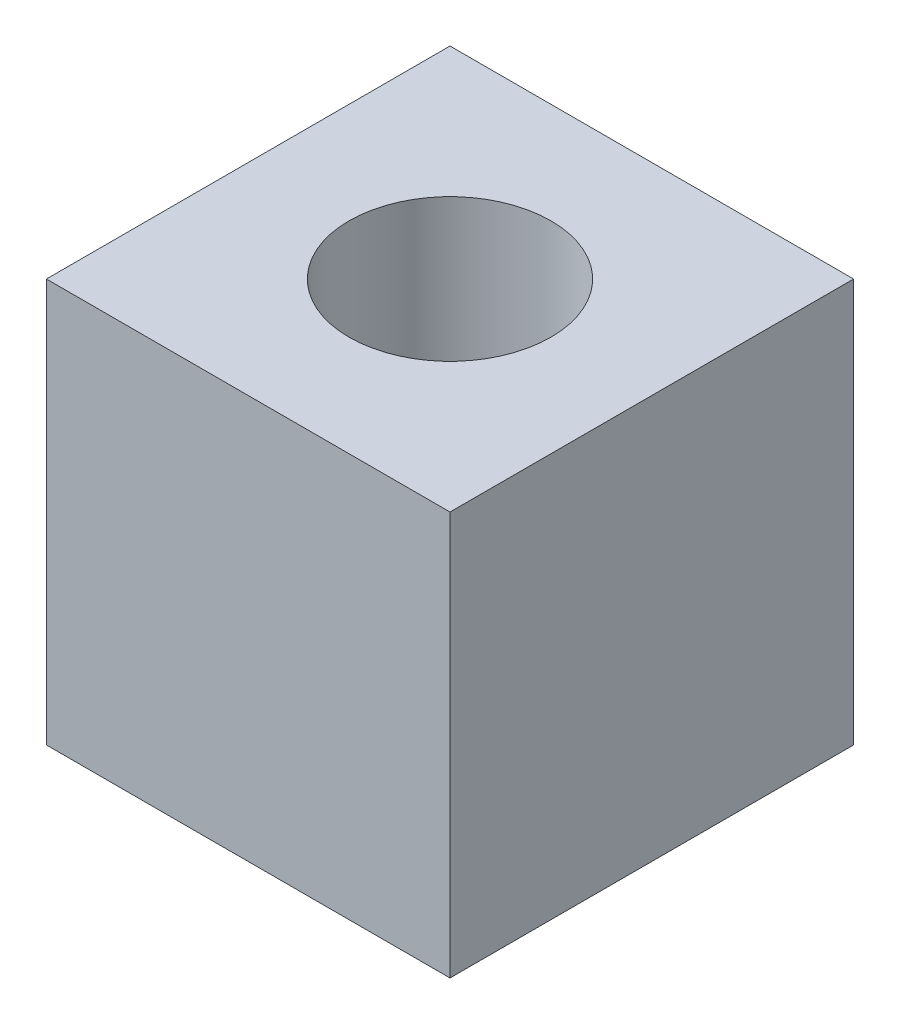
SolidWorks part; units mm, degrees
ref_plane "Front Plane" through (0, 0, 0) normal (0, 0, 1) x (1, 0, 0)
ref_plane "Top Plane" through (0, 0, 0) normal (0, 1, 0) x (1, 0, 0)
ref_plane "Right Plane" through (0, 0, 0) normal (1, 0, 0) x (0, 0, -1)
sketch "Sketch1" plane through (0, 0, 0) normal (0, 1, 0) x (1, 0, 0)
  line L1 (-6.35, 6.35) -> (6.35, 6.35)
  line L2 (-6.35, 6.35) -> (-6.35, -6.35)
  line L3 (-6.35, -6.35) -> (6.35, -6.35)
  line L4 (6.35, 6.35) -> (6.35, -6.35)
  line L5 (-6.35, 6.35) -> (6.35, -6.35) construction
  line L6 (-6.35, -6.35) -> (6.35, 6.35) construction
  point P0 (0, 0)
  dimension "D1" = 12.7
  dimension "D2" = 12.7
extrude "Boss-Extrude1" add sketch "Sketch1" along normal blind 12.7
sketch "Sketch2" plane through (0, 0, 0) normal (0, -1, 0) x (-1, 0, 0)
  circle A0 centre (0, 0) radius 3.175
  dimension "D1" = 6.35
extrude "Cut-Extrude1" cut sketch "Sketch2" against normal blind 16.51
